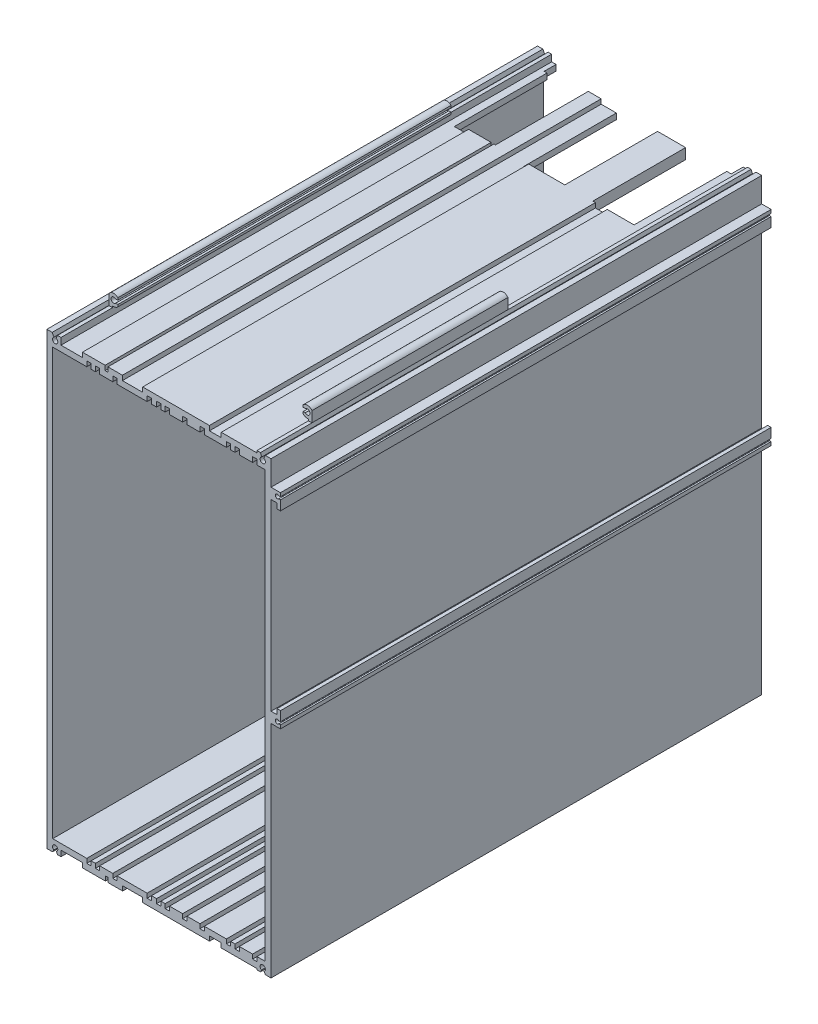
SolidWorks part; units mm, degrees
ref_plane "Front Plane" through (0, 0, 0) normal (0, 0, 1) x (1, 0, 0)
ref_plane "Top Plane" through (0, 0, 0) normal (0, 1, 0) x (1, 0, 0)
ref_plane "Right Plane" through (0, 0, 0) normal (1, 0, 0) x (0, 0, -1)
sketch "Sketch2" plane through (0, 0, 0) normal (0, 0, 1) x (1, 0, 0)
  line L0 (23.2732, 131.1707) -> (119.1108, 131.6725) construction
  line L1 (14.5, 261.3734) -> (14.5, 257.5858)
  line L2 (14.5, 257.5858) -> (26.7, 257.5858)
  line L3 (26.7, 257.5858) -> (26.7, 260.24)
  line L4 (26.7, 260.24) -> (39.5, 260.24)
  line L5 (39.5, 260.24) -> (39.5, 257.5858)
  line L6 (39.5, 257.5858) -> (41.1, 257.5858)
  line L7 (41.1, 257.5858) -> (41.1, 260.24)
  line L8 (41.1, 260.24) -> (49.3, 260.24)
  line L9 (49.3, 260.24) -> (49.3, 257.5858)
  line L10 (49.3, 257.5858) -> (60.8, 257.5858)
  line L11 (60.8, 257.5858) -> (60.8, 260.24)
  line L12 (60.8, 260.24) -> (98.6, 260.24)
  line L13 (98.6, 260.24) -> (98.6, 257.5858)
  line L14 (98.6, 257.5858) -> (105.3, 257.5858)
  line L15 (105.3, 257.5858) -> (105.3, 260.24)
  line L16 (105.3, 260.24) -> (125.5, 260.24)
  line L17 (125.5, 260.24) -> (125.5, 261.3734)
  line L18 (125.5, 261.3734) -> (127.5, 261.3734)
  line L19 (133.5, 261.3734) -> (133.5, 247.3734)
  line L20 (133.5, 247.3734) -> (138.85, 247.3734)
  line L21 (138.85, 247.3734) -> (138.85, 238.4234)
  line L22 (138.85, 238.4234) -> (136.9, 238.4234)
  line L23 (136.9, 238.4234) -> (136.9, 241.3734)
  line L24 (136.9, 241.3734) -> (133.5, 241.3734)
  line L25 (133.5, 241.3734) -> (133.5, 137.4734)
  line L26 (133.5, 137.4734) -> (136.9, 137.4734)
  line L27 (136.9, 137.4734) -> (136.9, 140.4234)
  line L28 (136.9, 140.4234) -> (138.85, 140.4234)
  line L29 (138.85, 140.4234) -> (138.85, 131.4734)
  line L30 (138.85, 131.4734) -> (133.5, 131.4734)
  line L31 (133.5, 131.4734) -> (133.5, 6.5734)
  line L32 (133.5, 6.5734) -> (130.3, 6.5734)
  line L33 (125.5, 6.5734) -> (125.5, 7.202)
  line L34 (125.5, 7.202) -> (105.25, 7.202)
  line L35 (105.25, 7.202) -> (105.25, 9.7858)
  line L36 (105.25, 9.7858) -> (98.65, 9.7858)
  line L37 (98.65, 9.7858) -> (98.65, 7.202)
  line L38 (98.65, 7.202) -> (60.55, 7.202)
  line L39 (60.55, 7.202) -> (60.55, 9.7858)
  line L40 (60.55, 9.7858) -> (49.45, 9.7858)
  line L41 (49.45, 9.7858) -> (49.45, 7.202)
  line L42 (49.45, 7.202) -> (41.2, 7.202)
  line L43 (41.2, 7.202) -> (41.2, 9.7858)
  line L44 (41.2, 9.7858) -> (39.6964, 9.7858)
  line L45 (39.6964, 9.7858) -> (39.6964, 7.202)
  line L46 (39.6964, 7.202) -> (26.5964, 7.202)
  line L47 (26.5964, 7.202) -> (26.5964, 9.7858)
  line L48 (26.5964, 9.7858) -> (14.4964, 9.7858)
  line L49 (14.4964, 9.7858) -> (14.4964, 6.5734)
  line L50 (14.4964, 6.5734) -> (12.4964, 6.5734)
  line L51 (6.5, 6.5734) -> (6.5, 261.3734)
  line L52 (6.5, 261.3734) -> (9.5, 261.3734)
  line L53 (9.8, 254.2858) -> (29.1, 254.2858)
  line L54 (29.1, 254.2858) -> (29.1, 257.1858)
  line L55 (29.1, 257.1858) -> (31.55, 257.1858)
  line L56 (31.55, 257.1858) -> (31.55, 254.2858)
  line L57 (31.55, 254.2858) -> (34, 254.2858)
  line L58 (34, 254.2858) -> (34, 257.1858)
  line L59 (34, 257.1858) -> (36.45, 257.1858)
  line L60 (36.45, 257.1858) -> (36.45, 254.2858)
  line L61 (36.45, 254.2858) -> (43.85, 254.2858)
  line L62 (43.85, 254.2858) -> (43.85, 257.1858)
  line L63 (43.85, 257.1858) -> (46.3, 257.1858)
  line L64 (46.3, 257.1858) -> (46.3, 254.2858)
  line L65 (46.3, 254.2858) -> (63.3, 254.2858)
  line L66 (63.3, 254.2858) -> (63.3, 257.1858)
  line L67 (63.3, 257.1858) -> (65.75, 257.1858)
  line L68 (65.75, 257.1858) -> (65.75, 254.2858)
  line L69 (65.75, 254.2858) -> (68.65, 254.2858)
  line L70 (68.65, 254.2858) -> (68.65, 257.1858)
  line L71 (68.65, 257.1858) -> (71.1, 257.1858)
  line L72 (71.1, 257.1858) -> (71.1, 254.2858)
  line L73 (71.1, 254.2858) -> (73.55, 254.2858)
  line L74 (73.55, 254.2858) -> (73.55, 257.1858)
  line L75 (73.55, 257.1858) -> (76, 257.1858)
  line L76 (76, 257.1858) -> (76, 254.2858)
  line L77 (76, 254.2858) -> (83.4, 254.2858)
  line L78 (83.4, 254.2858) -> (83.4, 257.1858)
  line L79 (83.4, 257.1858) -> (85.85, 257.1858)
  line L80 (85.85, 257.1858) -> (85.85, 254.2858)
  line L81 (85.85, 254.2858) -> (93.25, 254.2858)
  line L82 (93.25, 254.2858) -> (93.25, 257.1858)
  line L83 (93.25, 257.1858) -> (95.7, 257.1858)
  line L84 (95.7, 257.1858) -> (95.7, 254.2858)
  line L85 (95.7, 254.2858) -> (108.2, 254.2858)
  line L86 (108.2, 254.2858) -> (108.2, 257.1858)
  line L87 (108.2, 257.1858) -> (110.65, 257.1858)
  line L88 (110.65, 257.1858) -> (110.65, 254.2858)
  line L89 (110.65, 254.2858) -> (113.1, 254.2858)
  line L90 (113.1, 254.2858) -> (113.1, 257.1858)
  line L91 (113.1, 257.1858) -> (115.55, 257.1858)
  line L92 (115.55, 257.1858) -> (115.55, 254.2858)
  line L93 (115.55, 254.2858) -> (123.05, 254.2858)
  line L94 (123.05, 254.2858) -> (123.05, 257.1858)
  line L95 (123.05, 257.1858) -> (125.5, 257.1858)
  line L96 (125.5, 257.1858) -> (125.5, 254.2858)
  line L97 (125.5, 254.2858) -> (130.2, 254.2858)
  line L98 (130.2, 254.2858) -> (130.2, 13.0858)
  line L99 (130.2, 13.0858) -> (125.5, 13.0858)
  line L100 (125.5, 13.0858) -> (125.5, 10.6056)
  line L101 (125.5, 10.6056) -> (123.05, 10.6056)
  line L102 (123.05, 10.6056) -> (123.05, 13.0858)
  line L103 (123.05, 13.0858) -> (115.55, 13.0858)
  line L104 (115.55, 13.0858) -> (115.55, 10.6056)
  line L105 (115.55, 10.6056) -> (113.1, 10.6056)
  line L106 (113.1, 10.6056) -> (113.1, 13.0858)
  line L107 (113.1, 13.0858) -> (110.65, 13.0858)
  line L108 (110.65, 13.0858) -> (110.65, 10.6056)
  line L109 (110.65, 10.6056) -> (108.2, 10.6056)
  line L110 (108.2, 10.6056) -> (108.2, 13.0858)
  line L111 (108.2, 13.0858) -> (95.7, 13.0858)
  line L112 (95.7, 13.0858) -> (95.7, 10.6056)
  line L113 (95.7, 10.6056) -> (93.25, 10.6056)
  line L114 (93.25, 10.6056) -> (93.25, 13.0858)
  line L115 (93.25, 13.0858) -> (85.85, 13.0858)
  line L116 (85.85, 13.0858) -> (85.85, 10.6056)
  line L117 (85.85, 10.6056) -> (83.4, 10.6056)
  line L118 (83.4, 10.6056) -> (83.4, 13.0858)
  line L119 (83.4, 13.0858) -> (76, 13.0858)
  line L120 (76, 13.0858) -> (76, 10.6056)
  line L121 (76, 10.6056) -> (73.55, 10.6056)
  line L122 (73.55, 10.6056) -> (73.55, 13.0858)
  line L123 (73.55, 13.0858) -> (71.1, 13.0858)
  line L124 (71.1, 13.0858) -> (71.1, 10.6056)
  line L125 (71.1, 10.6056) -> (68.65, 10.6056)
  line L126 (68.65, 10.6056) -> (68.65, 13.0858)
  line L127 (68.65, 13.0858) -> (65.75, 13.0858)
  line L128 (65.75, 13.0858) -> (65.75, 10.6056)
  line L129 (65.75, 10.6056) -> (63.3, 10.6056)
  line L130 (63.3, 10.6056) -> (63.3, 13.0858)
  line L131 (63.3, 13.0858) -> (46.3, 13.0858)
  line L132 (46.3, 13.0858) -> (46.3, 10.6056)
  line L133 (46.3, 10.6056) -> (43.85, 10.6056)
  line L134 (43.85, 10.6056) -> (43.85, 13.0858)
  line L135 (43.85, 13.0858) -> (36.45, 13.0858)
  line L136 (36.45, 13.0858) -> (36.45, 10.6056)
  line L137 (36.45, 10.6056) -> (34, 10.6056)
  line L138 (34, 10.6056) -> (34, 13.0858)
  line L139 (34, 13.0858) -> (31.55, 13.0858)
  line L140 (31.55, 13.0858) -> (31.55, 10.6056)
  line L141 (31.55, 10.6056) -> (29.1, 10.6056)
  line L142 (29.1, 10.6056) -> (29.1, 13.0858)
  line L143 (29.1, 13.0858) -> (9.8, 13.0858)
  line L144 (9.8, 13.0858) -> (9.8, 254.2858)
  line L145 (11.2, 258.1858) -> (12.5, 261.3734)
  line L146 (11.2, 258.1858) -> (9.5, 261.3734)
  line L147 (12.5, 261.3734) -> (14.5, 261.3734)
  line L148 (128.8, 258.1858) -> (127.5, 261.3734)
  line L149 (128.8, 258.1858) -> (130.3, 261.3734)
  line L150 (130.3, 261.3734) -> (133.5, 261.3734)
  line L151 (138.85, 245.3734) -> (137.9352, 245.3734)
  line L152 (138.85, 243.8734) -> (137.8905, 243.8734)
  line L153 (138.85, 133.4734) -> (137.9352, 133.4734)
  line L154 (138.85, 134.9734) -> (137.8905, 134.9734)
  line L155 (128.8, 9.1858) -> (130.3, 6.5734)
  line L156 (128.8, 9.1858) -> (127.5, 6.5734)
  line L157 (127.5, 6.5734) -> (125.5, 6.5734)
  line L158 (11.2, 9.1858) -> (12.4964, 6.5734)
  line L159 (11.2, 9.1858) -> (9.7, 6.5734)
  line L160 (9.7, 6.5734) -> (6.5, 6.5734)
  circle A1 centre (11.2, 258.1858) radius 1.5
  circle A2 centre (128.8, 258.1858) radius 1.5
  circle A3 centre (137.075, 244.6484) radius 1.125
  circle A4 centre (137.075, 134.1984) radius 1.125
  circle A5 centre (128.8, 9.1858) radius 1.5
  circle A6 centre (11.2, 9.1858) radius 1.5
  point P51 (54.8, 13.0858)
  dimension "D1" = 127
  dimension "D87" = 3.2
  dimension "D90" = 3
  dimension "D92" = 2.4
  dimension "D93" = 3
  dimension "D97" = 5.75
  dimension "D101" = 5.75
  dimension "D106" = 3
  dimension "D111" = 3
  dimension "D2" = 3.3
  dimension "D3" = 3.3
  dimension "D4" = 120.4
  dimension "D5" = 8
  dimension "D6" = 8
  dimension "D7" = 3.3
  dimension "D8" = 3.3
  dimension "D9" = 254.8
  dimension "D10" = 247.8
  dimension "D11" = 241.2
  dimension "D12" = 12.2
  dimension "D13" = 12.8
  dimension "D14" = 1.6
  dimension "D15" = 37.8
  dimension "D16" = 8.2
  dimension "D17" = 11.5
  dimension "D18" = 6.7
  dimension "D19" = 20.2
  dimension "D20" = 19.3
  dimension "D21" = 2.9
  dimension "D22" = 2.45
  dimension "D23" = 2.45
  dimension "D24" = 2.45
  dimension "D25" = 2.45
  dimension "D26" = 2.45
  dimension "D27" = 2.45
  dimension "D28" = 2.45
  dimension "D29" = 2.45
  dimension "D30" = 2.45
  dimension "D31" = 2.45
  dimension "D32" = 2.45
  dimension "D33" = 2.45
  dimension "D34" = 7.4
  dimension "D35" = 17
  dimension "D36" = 19.3
  dimension "D37" = 2.9
  dimension "D38" = 2.45
  dimension "D39" = 7.4
  dimension "D40" = 7.4
  dimension "D41" = 12.5
  dimension "D42" = 2.45
  dimension "D43" = 7.5
  dimension "D44" = 4.7
  dimension "D45" = 2.45
  dimension "D46" = 2.45
  dimension "D47" = 2.45
  dimension "D48" = 7.4
  dimension "D49" = 2.45
  dimension "D50" = 17
  dimension "D51" = 2.45
  dimension "D52" = 2.9
  dimension "D53" = 2.45
  dimension "D54" = 2.45
  dimension "D55" = 2.45
  dimension "D56" = 7.4
  dimension "D57" = 2.45
  dimension "D58" = 7.4
  dimension "D59" = 2.45
  dimension "D60" = 12.5
  dimension "D61" = 2.45
  dimension "D62" = 2.45
  dimension "D63" = 2.45
  dimension "D64" = 7.5
  dimension "D65" = 2.45
  dimension "D66" = 4.7
  dimension "D67" = 7.9964
  dimension "D68" = 12.1
  dimension "D69" = 13.1
  dimension "D70" = 8.25
  dimension "D71" = 11.1
  dimension "D72" = 38.1
  dimension "D73" = 6.6
  dimension "D74" = 20.25
  dimension "D75" = 8
  dimension "D76" = 14
  dimension "D77" = 6
  dimension "D78" = 8.95
  dimension "D79" = 3.4
  dimension "D80" = 1.95
  dimension "D81" = 6
  dimension "D82" = 8.95
  dimension "D83" = 3.4
  dimension "D84" = 1.95
  dimension "D85" = 5.35
  dimension "D86" = 103.9
  dimension "D88" = 2.4
  dimension "D89" = 3
  dimension "D91" = 2
  dimension "D94" = 3.2
  dimension "D95" = 2
  dimension "D96" = 3.2
  dimension "D98" = 1.6
  dimension "D99" = 2
  dimension "D100" = 5.45
  dimension "D102" = 1.6
  dimension "D103" = 2
  dimension "D104" = 5.45
  dimension "D105" = 1.5
  dimension "D107" = 2.4
  dimension "D108" = 3.2
  dimension "D109" = 2
  dimension "D110" = 3.2
  dimension "D112" = 2.4
  dimension "D113" = 3.2
  dimension "D114" = 3.2
  dimension "D115" = 2
extrude "Boss-Extrude1" add sketch "Sketch2" along normal blind 278 contours A6 L158 L50 L49 L48 L47 L46 L45 L44 L43 L42 L41 L40 L39 L38 L37 L36 L35 L34 L33 L157 L156 A5 L155 L32 L31 L30 L29 L153 A4 L154 L28 L27 L26 L25 L24 L23 L22 L21 L152 A3 L151 L20 L19 L150 L149 A2 L148 L18
ref_plane "Plane1" through (0, 0, 60) normal (0, 0, -1) x (-1, 0, 0)
sketch "Sketch3" plane through (0, 0, 60) normal (0, 0, -1) x (-1, 0, 0)
  line L0 (-127.5, 261.3734) -> (-127.5, 267.3734)
  line L1 (-122.5, 270.1784) -> (-122.5, 262.1784)
  line L2 (-125.5, 261.3734) -> (-125.5, 269.0865)
  line L3 (-121.7757, 266.54) -> (-123.9222, 266.54)
  line L4 (-121.7757, 264.44) -> (-123.7503, 264.44)
  line L5 (-133.5, 251.3903) -> (-6.5, 251.3903) construction
  line L6 (-133.5, 261.3734) -> (-133.5, 247.3734) construction
  line L7 (-6.5, 6.5734) -> (-6.5, 261.3734) construction
  line L8 (-105.3, 260.24) -> (-125.5, 260.24) construction
  line L10 (-70, 251.3903) -> (-70, 270.1784) construction
  line L11 (-14.5, 261.3734) -> (-14.5, 269.0865)
  line L12 (-12.5, 261.3734) -> (-12.5, 267.3734)
  line L13 (-18.2243, 264.44) -> (-16.2497, 264.44)
  line L14 (-18.2243, 266.54) -> (-16.0778, 266.54)
  line L15 (-17.5, 270.1784) -> (-17.5, 262.1784)
  line L16 (-127.5, 261.3734) -> (-125.5, 261.3734)
  line L17 (-14.5, 261.3734) -> (-12.5, 261.3734)
  circle A0 centre (-124.8514, 265.49) radius 3.25
  circle A2 centre (-124.9004, 265.4028) radius 1.5
  circle A6 centre (-15.0996, 265.4028) radius 1.5
  circle A7 centre (-15.1486, 265.49) radius 3.25
  dimension "D1" = 6.5
  dimension "D5" = 3
  dimension "D6" = 1.85
  dimension "D2" = 5
  dimension "D3" = 6
  dimension "D4" = 2
  dimension "D7" = 2.2
  dimension "D8" = 2.2
extrude "Boss-Extrude2" add sketch "Sketch3" against normal blind 188.8 contours A7 L11 A6 L13 L15 | A7 L12 L11 A6 | L12 A7 L11 L17 | A7 L15 L14 A6 L11 | A0 L0 L16 L2 | A2 L2 A0 L0 | A2 L3 L1 A0 L2 | A2 L2 A0 L1 L4
sketch "Sketch4" plane through (127.5, 0, 0) normal (1, 0, 0) x (0, 0, -1)
  line L0 (-248.8, 261.3734) -> (-248.8, 267.3734) construction
  line L5 (-60, 261.3734) -> (-137.8, 261.3734)
  line L6 (-60, 261.3734) -> (-60, 282.1971)
  line L7 (-60, 282.1971) -> (-137.8, 282.1971)
  line L8 (-137.8, 261.3734) -> (-137.8, 282.1971)
  line L9 (-60, 261.3734) -> (-137.8, 282.1971) construction
  line L10 (-60, 282.1971) -> (-137.8, 261.3734) construction
  point P4 (-98.9, 271.7852)
  dimension "D1" = 111
extrude "Cut-Extrude3" cut sketch "Sketch4" against normal up to next
sketch "Sketch5" plane through (0, 260.24, 0) normal (0, 1, 0) x (1, 0, 0)
  line L0 (105.3, 0) -> (125.5, 0) construction
  line L1 (17, -6.75) -> (123, -6.75)
  line L2 (17, -6.75) -> (17, 0)
  line L3 (17, 0) -> (123, 0)
  line L4 (123, -6.75) -> (123, 0)
  line L5 (17, -6.75) -> (123, 0) construction
  line L6 (17, 0) -> (123, -6.75) construction
  line L7 (14.5, -60) -> (14.5, 0) construction
  line L8 (125.5, -137.8) -> (125.5, 0) construction
  point P4 (70, -3.375)
  dimension "D1" = 106
  dimension "D2" = 2.5
  dimension "D3" = 6.75
  dimension "D4" = 2.5
extrude "Cut-Extrude4" cut sketch "Sketch5" against normal up to next
sketch "Sketch6" plane through (0, 260.24, 0) normal (0, 1, 0) x (1, 0, 0)
  line L0 (105.3, -6.75) -> (123, -6.75) construction
  line L1 (120.5, -6.75) -> (97.15, -6.75)
  line L2 (120.5, -6.75) -> (120.5, -59.3)
  line L3 (120.5, -59.3) -> (97.15, -59.3)
  line L4 (97.15, -6.75) -> (97.15, -59.3)
  line L5 (120.5, -6.75) -> (97.15, -59.3) construction
  line L6 (120.5, -59.3) -> (97.15, -6.75) construction
  line L7 (125.5, -278) -> (125.5, 0) construction
  line L8 (133.5, 0) -> (138.85, 0) construction
  line L9 (60.8, -6.75) -> (98.6, -6.75) construction
  line L10 (81.25, -6.75) -> (57.9, -6.75)
  line L11 (81.25, -6.75) -> (81.25, -59.3)
  line L12 (81.25, -59.3) -> (57.9, -59.3)
  line L13 (57.9, -6.75) -> (57.9, -59.3)
  line L14 (81.25, -6.75) -> (57.9, -59.3) construction
  line L15 (81.25, -59.3) -> (57.9, -6.75) construction
  line L16 (60.8, -6.75) -> (49.3, -6.75) construction
  line L17 (42, -6.75) -> (18.65, -6.75)
  line L18 (42, -6.75) -> (42, -59.3)
  line L19 (42, -59.3) -> (18.65, -59.3)
  line L20 (18.65, -6.75) -> (18.65, -59.3)
  line L21 (42, -6.75) -> (18.65, -59.3) construction
  line L22 (42, -59.3) -> (18.65, -6.75) construction
  point P4 (108.825, -33.025)
  point P15 (69.575, -33.025)
  point P22 (30.325, -33.025)
  dimension "D1" = 23.35
  dimension "D2" = 5
  dimension "D3" = 52.55
  dimension "D4" = 59.3
  dimension "D5" = 52.55
  dimension "D6" = 15.9
  dimension "D7" = 23.35
  dimension "D8" = 23.35
  dimension "D9" = 15.9
extrude "Cut-Extrude5" cut sketch "Sketch6" against normal up to next
